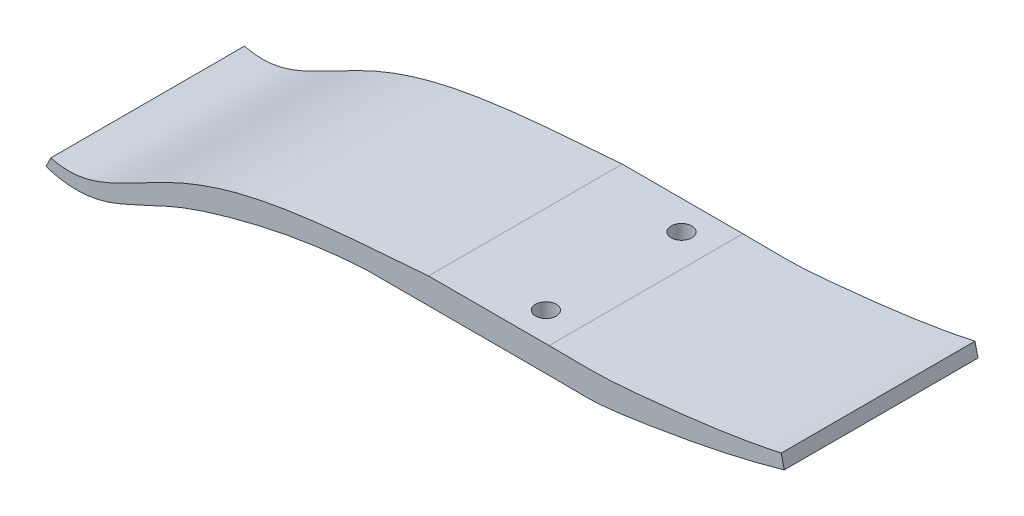
SolidWorks part; units mm, degrees
ref_plane "Piano frontale" through (0, 0, 0) normal (0, 0, 1) x (1, 0, 0)
ref_plane "Piano superiore" through (0, 0, 0) normal (0, 1, 0) x (1, 0, 0)
ref_plane "Piano destro" through (0, 0, 0) normal (1, 0, 0) x (0, 0, -1)
sketch "Schizzo1" plane through (0, 0, 0) normal (0, 0, 1) x (1, 0, 0)
  line L0 (0, 0) -> (150, 0)
  line L1 (-321.1596, 15.9937) -> (-560.6113, 796.7672) construction
  line L2 (-4.3491, -26.8408) -> (-3.9663, -26.937)
  line L3 (-51.9474, 387.4316) -> (764.7193, 387.4316) construction
  line L4 (-5.8196, -29.8434) -> (-4.3491, -26.8408)
  line L5 (221.8951, 7.1301) -> (222.8247, 3.0623)
  line L6 (93.1769, -8) -> (150, -8)
  spline S0 degree 3 poles (112.6528, 0) (98.2377, -1.1782) (76.3254, -2.3671) (50.3861, -7.7153) (33.0349, -14.2602) (16.9038, -23.444) (3.8284, -28.9701) (-4.3491, -26.8408) knots 0 0 0 0 0.357718 0.541412 0.651992 0.814468 1 1 1 1
  spline S1 degree 3 poles (93.1769, -8) (78.0958, -8.807) (58.5152, -12.4651) (33.4259, -20.4928) (21.8686, -26.5918) (8.4687, -31.8499) (-0.0208, -31.918) (-5.8196, -29.8434) knots 0 0 0 0 0.439768 0.579666 0.76758 0.820027 1 1 1 1
  spline S2 degree 3 poles (150, 0) (155.1864, -0.0719) (162.776, -0.1927) (171.9425, 0.1981) (191.0542, 2.0423) (208.371, 4.1609) (221.8951, 7.1301) knots 0 0 0 0 0.180513 0.221559 0.410457 1 1 1 1
  spline S3 degree 3 poles (150, -8) (160.9347, -8.1785) (167.7326, -7.9814) (191.2182, -4.4007) (208.8639, -0.958) (222.8247, 3.0623) knots 0 0 0 0 0.132806 0.367169 1 1 1 1
  point P5 (0, 0)
  dimension "D1" = 150
  dimension "D2" = 231
extrude "Estrusione-Estrusione1" add sketch "Schizzo1" against normal blind 60 contours L6 S3 L5 S2 L0 S0 L4 S1
sketch "Schizzo2" plane through (0, 0, 0) normal (0, 1, 0) x (1, 0, 0)
  line L0 (140, 65.3766) -> (140, -9.0702) construction
  line L1 (131.5646, 51) -> (144.2572, 51) construction
  line L2 (112.6528, 30) -> (150, 30) construction
  line L3 (112.6528, 60) -> (112.6528, 0) construction
  line L4 (150, 60) -> (150, 0) construction
  line L5 (112.6528, 60) -> (150, 60) construction
  circle A0 centre (140, 51) radius 3.2
  circle A1 centre (140, 9) radius 3.2
  point P14 (0, 0)
  dimension "D3" = 6.4
  dimension "D1" = 10
  dimension "D2" = 9
extrude "Taglio-Estrusione1" cut sketch "Schizzo2" against normal through all
